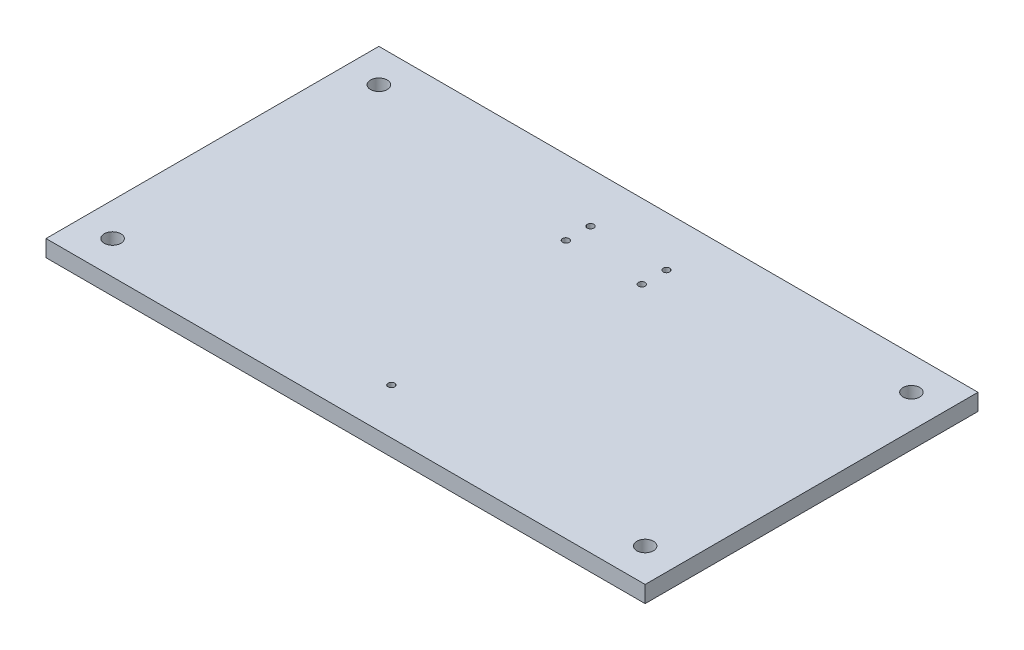
SolidWorks part; units mm, degrees
material "Brass"
ref_plane "Front Plane" through (0, 0, 0) normal (0, 0, 1) x (1, 0, 0)
ref_plane "Top Plane" through (0, 0, 0) normal (0, 1, 0) x (1, 0, 0)
ref_plane "Right Plane" through (0, 0, 0) normal (1, 0, 0) x (0, 0, -1)
sketch "Sketch1" plane through (0, 0, 0) normal (0, 1, 0) x (1, 0, 0)
  line L0 (76.2, -69.85) -> (76.2, 57.15) construction
  line L1 (-38.1, -69.85) -> (190.5, -69.85)
  line L2 (-38.1, -69.85) -> (-38.1, 57.15)
  line L3 (-38.1, 57.15) -> (190.5, 57.15)
  line L4 (190.5, -69.85) -> (190.5, 57.15)
  line L5 (-38.1, -69.85) -> (190.5, 57.15) construction
  line L6 (-38.1, 57.15) -> (190.5, -69.85) construction
  circle A0 centre (61.7131, 38.1) radius 1.27
  circle A1 centre (90.6869, 38.1) radius 1.27
  circle A2 centre (76.2, -52.3596) radius 1.27
  circle A3 centre (61.7131, 28.6995) radius 1.27
  circle A4 centre (90.6869, 28.6995) radius 1.27
  circle A5 centre (-25.4, 44.45) radius 3.175
  circle A6 centre (177.8, 44.45) radius 3.175
  circle A7 centre (177.8, -57.15) radius 3.175
  circle A8 centre (-25.4, -57.15) radius 3.175
  point P0 (76.2, -6.35)
  dimension "D1" = 2.54
  dimension "D8" = 6.35
  dimension "D11" = 2
  dimension "D2" = 228.6
  dimension "D3" = 127
  dimension "D4" = 28.9738
  dimension "D5" = 90.4596
  dimension "D6" = 9.4005
  dimension "D7" = 19.05
  dimension "D9" = 12.7
  dimension "D10" = 12.7
  dimension "D12" = 203.2
  dimension "D13" = 101.6
extrude "Boss-Extrude1" add sketch "Sketch1" along normal blind 6.35
